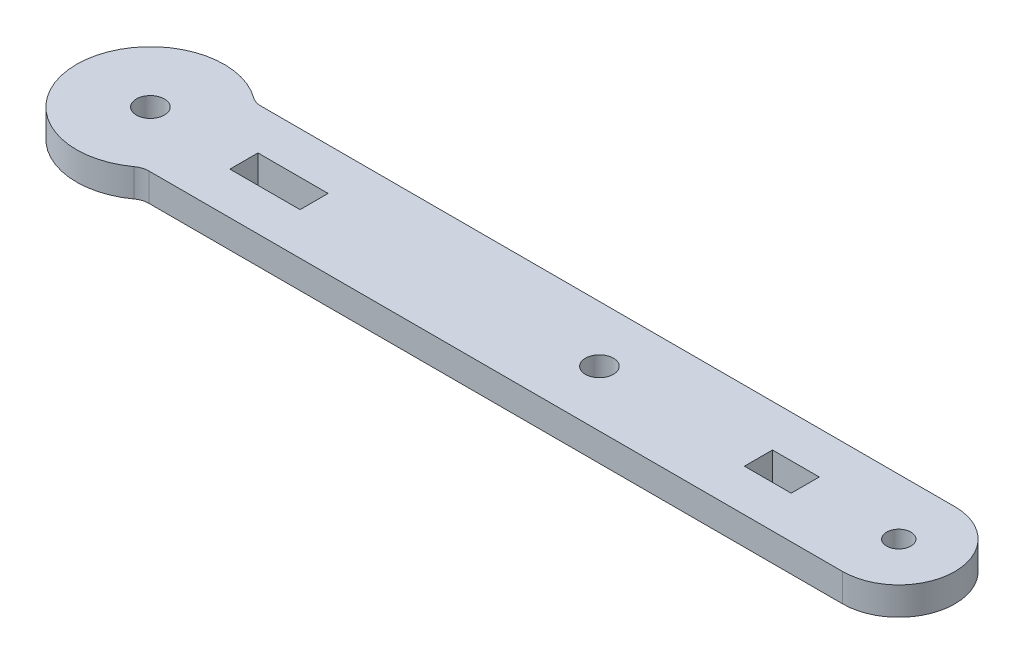
SolidWorks part; units mm, degrees
material "Acrílico (médio-alto impacto)"
ref_plane "Plano frontal" through (0, 0, 0) normal (0, 0, 1) x (1, 0, 0)
ref_plane "Plano superior" through (0, 0, 0) normal (0, 1, 0) x (1, 0, 0)
ref_plane "Plano direito" through (0, 0, 0) normal (1, 0, 0) x (0, 0, -1)
sketch "Esboço1" plane through (0, 0, 0) normal (0, 1, 0) x (1, 0, 0)
  line L0 (0, 0) -> (80, 0) construction
  line L1 (80, 6) -> (5.1391, 6)
  line L2 (80, -6) -> (5.1391, -6)
  circle A0 centre (0, 0) radius 7.9
  circle A1 centre (80, 0) radius 6
  point P9 (48, 0)
  dimension "D2" = 12
  dimension "D3" = 15.8
  dimension "D1" = 80
  dimension "D4" = 32
sketch "Esboço2" plane through (0, 0, 0) normal (0, 1, 0) x (1, 0, 0)
  line L0 (0, 0) -> (80, 0) construction
  line L1 (65, -1.5) -> (70, -1.5)
  line L2 (65, -1.5) -> (65, 1.5)
  line L3 (65, 1.5) -> (70, 1.5)
  line L4 (70, -1.5) -> (70, 1.5)
  line L5 (67.5, 1.5) -> (67.5, -1.5) construction
  line L6 (65, 0) -> (70, 0) construction
  line L8 (10, -1.5) -> (17.5, -1.5)
  line L9 (10, -1.5) -> (10, 1.5)
  line L10 (10, 1.5) -> (17.5, 1.5)
  line L11 (17.5, -1.5) -> (17.5, 1.5)
  line L12 (13.75, 1.5) -> (13.75, -1.5) construction
  line L13 (10, 0) -> (17.5, 0) construction
  point P0 (67.5, 0)
  point P6 (13.75, 0)
  dimension "D1" = 5
  dimension "D2" = 7.5
  dimension "D3" = 30.5
  dimension "D4" = 10
  dimension "D5" = 3
extrude "Ressalto-extrusão1" add sketch "Esboço1" along normal blind 3
extrude "Corte-extrusão1" cut sketch "Esboço2" along normal through all
hole_wizard "Furo de diâmetro Ø3.0 (3)1" positions "Esboço3" profile "Esboço4" hole size "Ø3.0" standard "ISO" end condition through all
sketch "Esboço3" plane through (0, 3, 0) normal (0, 1, 0) x (1, 0, 0)
  point P0 (0, 0)
  point P3 (48, 0)
sketch "Esboço4" plane through (0, 3, 0) normal (1, 0, 0) x (0, 0, 1)
  line L0 (0, 0) -> (0, 3)
  line L1 (0, 3) -> (1.5, 3)
  line L2 (1.5, 3) -> (1.5, 0)
  line L5 (1.5, 0) -> (0, 0)
  line L11 (0, -6.35) -> (0, 107.95) construction
  dimension "Thru Hole Dia." = 3
  dimension "Thru Hole Depth" = 3
hole_wizard "Furo de diâmetro Ø2.6 (2.6)1" positions "Esboço5" profile "Esboço6" hole size "Ø2.6" standard "ISO" end condition through all
sketch "Esboço5" plane through (0, 3, 0) normal (0, 1, 0) x (1, 0, 0)
  point P0 (80, 0)
sketch "Esboço6" plane through (80, 3, 0) normal (1, 0, 0) x (0, 0, 1)
  line L0 (0, 0) -> (0, 3)
  line L1 (0, 3) -> (1.3, 3)
  line L2 (1.3, 3) -> (1.3, 0)
  line L5 (1.3, 0) -> (0, 0)
  line L11 (0, -6.35) -> (0, 107.95) construction
  dimension "Thru Hole Dia." = 2.6
  dimension "Thru Hole Depth" = 3
fillet "Filete1" radius 2 2 edges at (5.1391, 1.5, 6) (5.1391, 1.5, -6)
